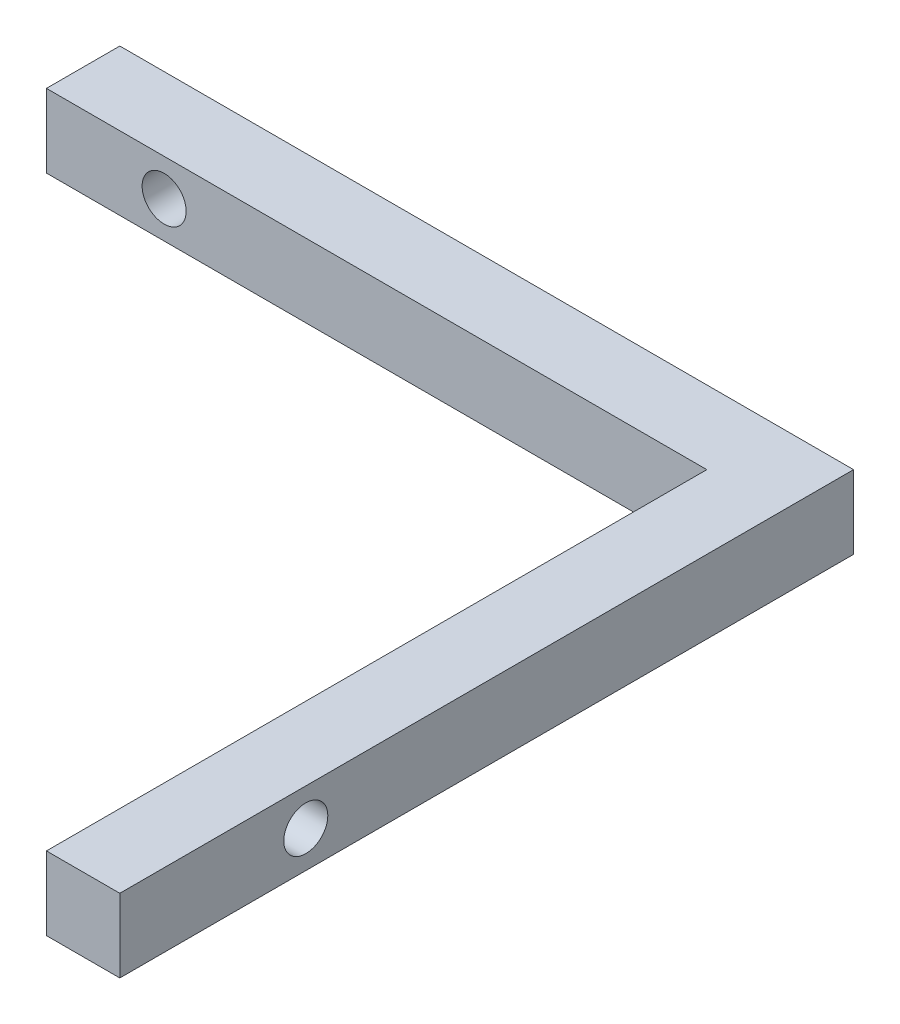
SolidWorks part; units mm, degrees
ref_plane "Ön Düzlem" through (0, 0, 0) normal (0, 0, 1) x (1, 0, 0)
ref_plane "Üst Düzlem" through (0, 0, 0) normal (0, 1, 0) x (1, 0, 0)
ref_plane "Sağ Düzlem" through (0, 0, 0) normal (1, 0, 0) x (0, 0, -1)
sketch "Çizim1" plane through (0, 0, 0) normal (0, 1, 0) x (1, 0, 0)
  line L1 (40, -5) -> (-50, -5)
  line L2 (50, -10) -> (50, 5)
  line L3 (50, 5) -> (-50, 5)
  line L4 (-50, -5) -> (-50, 5)
  line L5 (50, 5) -> (18.1918, 5)
  line L6 (50, 5) -> (50, -95)
  line L7 (50, -95) -> (40, -95)
  line L8 (40, -5) -> (40, -95)
  point P6 (0, 5)
  point P9 (-50, 0)
  dimension "D1" = 100
  dimension "D2" = 10
  dimension "D3" = 100
  dimension "D4" = 10
extrude "Yükseklik-Ekstrüzyon1" add sketch "Çizim1" along normal blind 10 contours L1 L8 L7 L6 L2 L3 L4
sketch "Çizim2" plane through (0, 0, -5) normal (0, 0, -1) x (-1, 0, 0)
  line L0 (-50, 0) -> (50, 0) construction
  circle A0 centre (33.9592, 5) radius 3
  dimension "D1" = 6
  dimension "D2" = 5
extrude "Kes-Ekstrüzyon1" cut sketch "Çizim2" against normal through all
sketch "Çizim3" plane through (50, 0, 0) normal (1, 0, 0) x (0, 0, -1)
  line L0 (5, 0) -> (-95, 0) construction
  circle A0 centre (-69.6525, 5) radius 3
  point P4 (-86.7405, 5)
  point P5 (-104.5592, 5)
  point P6 (-69.6525, 5)
  dimension "D1" = 6
  dimension "D2" = 5
extrude "Kes-Ekstrüzyon2" cut sketch "Çizim3" against normal through all
